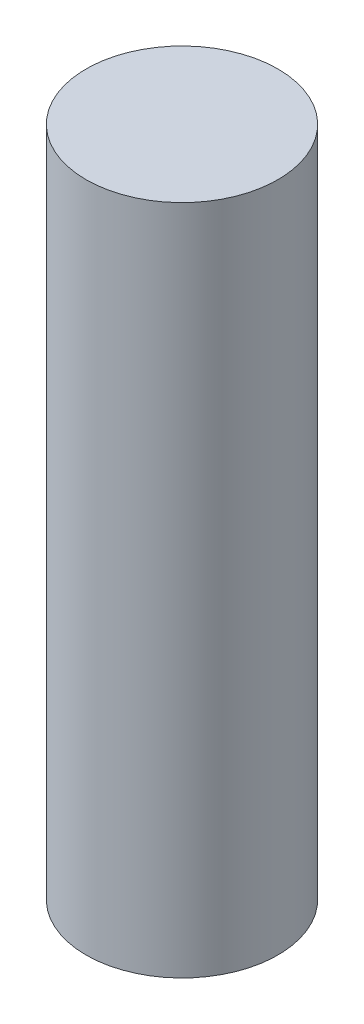
SolidWorks part; units mm, degrees
ref_plane "정면" through (0, 0, 0) normal (0, 0, 1) x (1, 0, 0)
ref_plane "윗면" through (0, 0, 0) normal (0, 1, 0) x (1, 0, 0)
ref_plane "우측면" through (0, 0, 0) normal (1, 0, 0) x (0, 0, -1)
sketch "스케치1" plane through (0, 0, 0) normal (0, 1, 0) x (1, 0, 0)
  circle A0 centre (0, 0) radius 5
  dimension "D1" = 10
extrude "보스-돌출1" add sketch "스케치1" along normal blind 35
